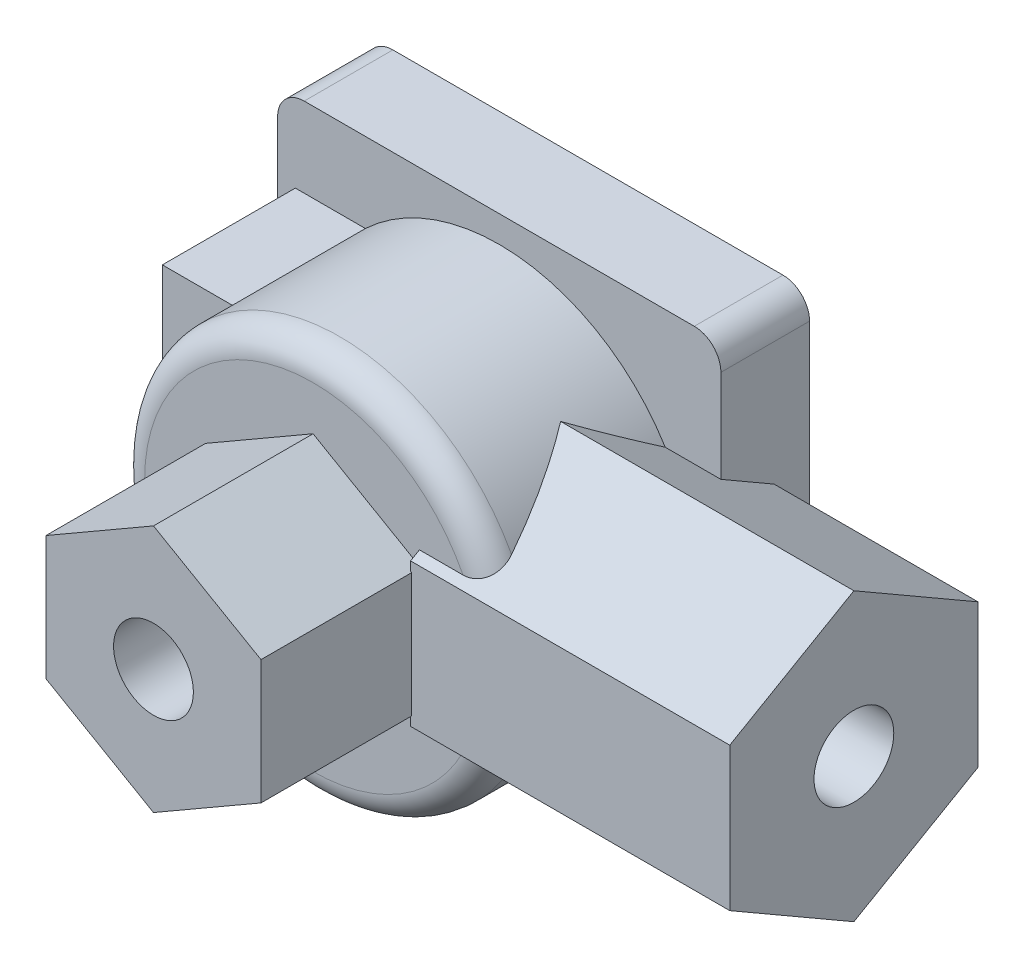
SolidWorks part; units mm, degrees
ref_plane "Front Plane" through (0, 0, 0) normal (0, 0, 1) x (1, 0, 0)
ref_plane "Top Plane" through (0, 0, 0) normal (0, 1, 0) x (1, 0, 0)
ref_plane "Right Plane" through (0, 0, 0) normal (1, 0, 0) x (0, 0, -1)
sketch "Sketch1" plane through (0, 0, 0) normal (0, 0, 1) x (1, 0, 0)
  line L1 (0, 50) -> (50, 50)
  line L2 (0, 50) -> (0, 0)
  line L3 (0, 0) -> (50, 0)
  line L4 (50, 50) -> (50, 0)
  dimension "D1" = 50
  dimension "D2" = 50
extrude "Boss-Extrude1" add sketch "Sketch1" along normal blind 10
sketch "Sketch2" plane through (0, 0, 10) normal (0, 0, 1) x (1, 0, 0)
  line L0 (25, 56.1658) -> (25, -8.5605) construction
  line L1 (-9.5478, 25) -> (79.8739, 25) construction
  circle A0 centre (25, 25) radius 22
  dimension "D1" = 44
extrude "Boss-Extrude2" add sketch "Sketch2" along normal blind 21
sketch "Sketch3" plane through (0, 0, 31) normal (0, 0, 1) x (1, 0, 0)
  line L0 (25, 50) -> (25, 0) construction
  line L1 (50, 50) -> (0, 50) construction
  line L2 (-6.146, 25) -> (63.6784, 25) construction
  line L5 (25, 11) -> (37.1244, 18)
  line L6 (37.1244, 18) -> (37.1244, 32)
  line L7 (37.1244, 32) -> (25, 39)
  line L8 (25, 39) -> (12.8756, 32)
  line L9 (12.8756, 32) -> (12.8756, 18)
  line L10 (12.8756, 18) -> (25, 11)
  circle A0 centre (25, 25) radius 12.1244 construction
  point P6 (25, 25)
  dimension "D1" = 14
  dimension "D2" = 25
  dimension "D3" = 25
extrude "Boss-Extrude3" add sketch "Sketch3" along normal blind 18
sketch "Sketch4" plane through (0, 0, 49) normal (0, 0, 1) x (1, 0, 0)
  line L0 (25, 50) -> (25, 0) construction
  line L1 (50, 50) -> (0, 50) construction
  line L2 (0, 0) -> (50, 0) construction
  line L3 (0, 25) -> (50, 25) construction
  line L4 (0, 50) -> (0, 0) construction
  line L5 (50, 0) -> (50, 50) construction
  circle A0 centre (25, 25) radius 4.5
  dimension "D1" = 9
extrude "Cut-Extrude1" cut sketch "Sketch4" against normal through all
sketch "Sketch6" plane through (0, 0, 0) normal (0, -1, 0) x (1, 0, 0)
  line L0 (2, 10) -> (2, 25)
  line L1 (0, 10) -> (50, 10) construction
  line L2 (2, 25) -> (10, 25)
  line L3 (10, 25) -> (10, 10)
  line L4 (10, 10) -> (2, 10)
  dimension "D1" = 2
  dimension "D2" = 8
  dimension "D3" = 15
extrude "Boss-Extrude4" add sketch "Sketch6" against normal blind 32 from offset 9 offset against normal yes
ref_plane "Plane1" through (73, 0, 0) normal (1, 0, 0) x (0, 0, -1)
sketch "Sketch10" plane through (73, 0, 0) normal (1, 0, 0) x (0, 0, -1)
  line L0 (-54.7238, 25) -> (5.107, 25) construction
  line L1 (-18, -6.5861) -> (-18, 73.1883) construction
  line L2 (0, 0) -> (0, 50) construction
  line L3 (-10, 0) -> (0, 0) construction
  line L4 (-4, 16.9171) -> (-4, 33.0829)
  line L5 (-4, 33.0829) -> (-18, 41.1658)
  line L6 (-18, 41.1658) -> (-32, 33.0829)
  line L7 (-32, 33.0829) -> (-32, 16.9171)
  line L8 (-32, 16.9171) -> (-18, 8.8342)
  line L9 (-18, 8.8342) -> (-4, 16.9171)
  circle A0 centre (-18, 25) radius 14 construction
  dimension "D3" = 25
  dimension "D1" = 18
  dimension "D2" = 28
extrude "Boss-Extrude5" add sketch "Sketch10" against normal blind 36
sketch "Sketch12" plane through (73, 0, 0) normal (1, 0, 0) x (0, 0, -1)
  line L0 (-32, 33.0829) -> (-32, 16.9171) construction
  line L3 (-32, 25) -> (-4, 25) construction
  line L4 (-4, 16.9171) -> (-4, 33.0829) construction
  line L5 (-18, 8.8342) -> (-18, 41.1658) construction
  circle A0 centre (-18, 25) radius 4.5
  dimension "D1" = 9
extrude "Cut-Extrude2" cut sketch "Sketch12" against normal blind 48
fillet "Fillet1" radius 3 1 edges at (3, 25, 31)
fillet "Fillet2" radius 3 4 edges at (50, 0, 5) (50, 50, 5) (0, 50, 5) (0, 0, 5)
